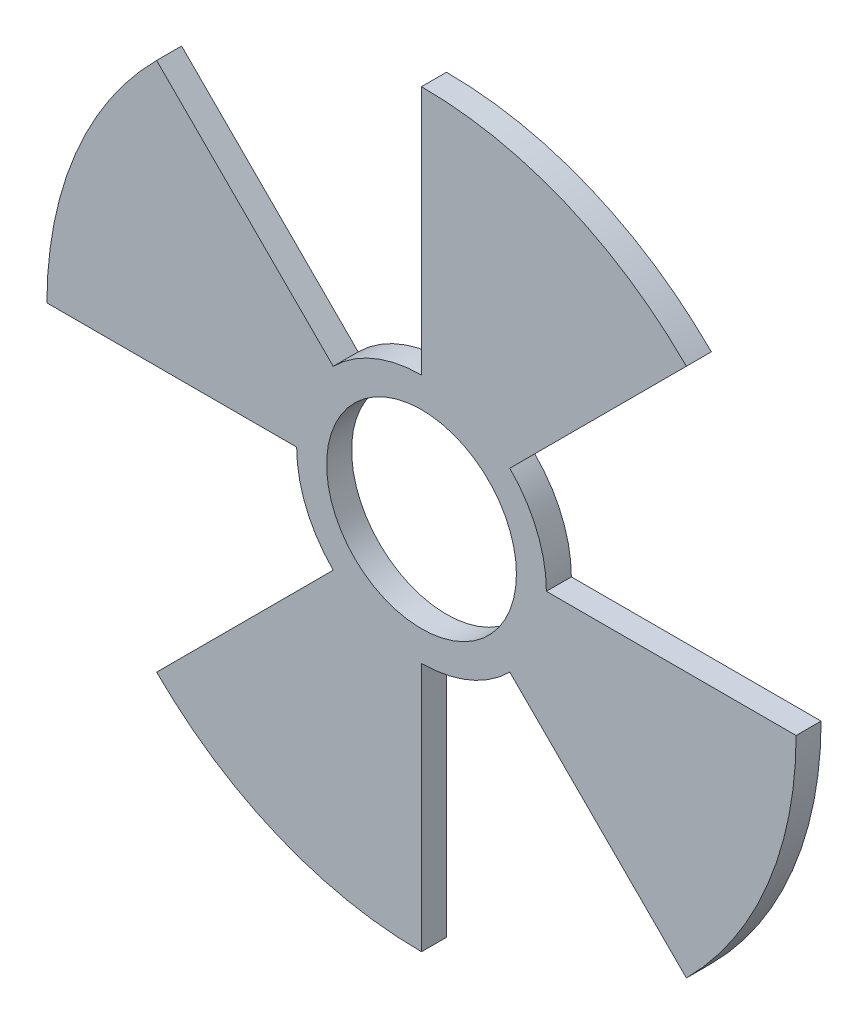
SolidWorks part; units mm, degrees
material "ABS"
ref_plane "正面" through (0, 0, 0) normal (0, 0, 1) x (1, 0, 0)
ref_plane "平面" through (0, 0, 0) normal (0, 1, 0) x (1, 0, 0)
ref_plane "右側面" through (0, 0, 0) normal (1, 0, 0) x (0, 0, -1)
sketch "ｽｹｯﾁ1" plane through (0, 0, 0) normal (0, 0, 1) x (1, 0, 0)
  circle A0 centre (0, 0) radius 7.6
  circle A1 centre (0, 0) radius 10
  dimension "D1" = 20
  dimension "D2" = 15.2
extrude "ﾎﾞｽ - 押し出し1" add sketch "ｽｹｯﾁ1" along normal blind 2
sketch "ｽｹｯﾁ2" plane through (0, 0, 2) normal (0, 0, 1) x (1, 0, 0)
  line L1 (21.2132, 21.2132) -> (0, 0) construction
  line L2 (0, 0) -> (0, 30) construction
  line L3 (0, 30) -> (0, 10)
  line L4 (21.2132, 21.2132) -> (7.0711, 7.0711)
  line L5 (21.2132, -21.2132) -> (7.0711, -7.0711)
  line L6 (30, 0) -> (10, 0)
  line L7 (-21.2132, -21.2132) -> (-7.0711, -7.0711)
  line L8 (0, -30) -> (0, -10)
  line L9 (-21.2132, 21.2132) -> (-7.0711, 7.0711)
  line L10 (-30, 0) -> (-10, 0)
  arc A0 (21.2132, 21.2132) -> (0, 30) centre (0, 0) ccw
  arc A1 (0, 10) -> (7.0711, 7.0711) centre (0, 0) cw
  circle A2 centre (0, 0) radius 10 construction
  arc A3 (10, 0) -> (7.0711, -7.0711) centre (0, 0) cw
  arc A4 (21.2132, -21.2132) -> (30, 0) centre (0, 0) ccw
  arc A5 (0, -10) -> (-7.0711, -7.0711) centre (0, 0) cw
  arc A6 (-21.2132, -21.2132) -> (0, -30) centre (0, 0) ccw
  arc A7 (-10, 0) -> (-7.0711, 7.0711) centre (0, 0) cw
  arc A8 (-21.2132, 21.2132) -> (-30, 0) centre (0, 0) ccw
  point P23 (0, 0)
  dimension "D1" = 45
  dimension "D2" = 30
  dimension "D3" = 4
extrude "ﾎﾞｽ - 押し出し2" add sketch "ｽｹｯﾁ2" against normal blind 2
